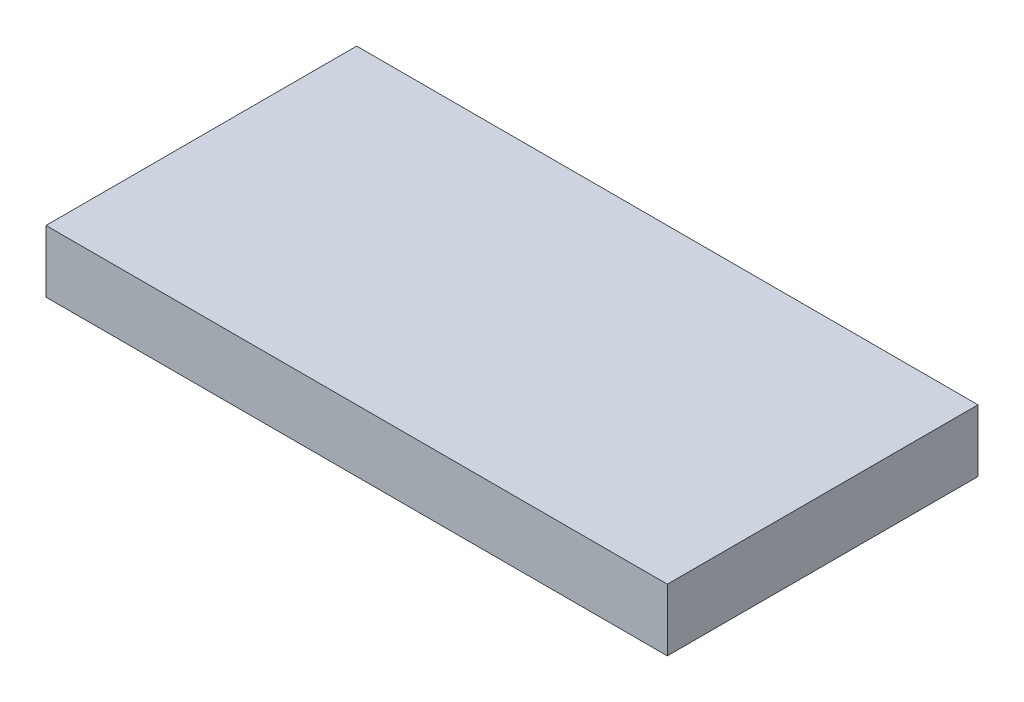
SolidWorks part; units mm, degrees
ref_plane "Front Plane" through (0, 0, 0) normal (0, 0, 1) x (1, 0, 0)
ref_plane "Top Plane" through (0, 0, 0) normal (0, 1, 0) x (1, 0, 0)
ref_plane "Right Plane" through (0, 0, 0) normal (1, 0, 0) x (0, 0, -1)
sketch "Sketch1" plane through (0, 0, 0) normal (0, 1, 0) x (1, 0, 0)
  line L1 (0, 0) -> (10, 0)
  line L2 (0, 0) -> (0, 5)
  line L3 (0, 5) -> (10, 5)
  line L4 (10, 0) -> (10, 5)
  dimension "D1" = 10
  dimension "D2" = 5
extrude "Boss-Extrude1" add sketch "Sketch1" along normal blind 1
